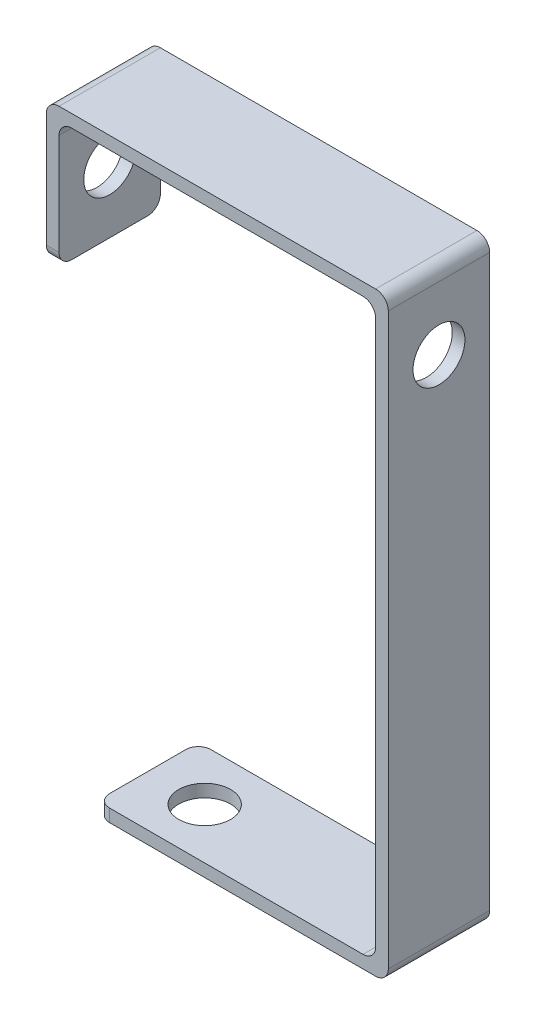
SolidWorks part; units mm, degrees
ref_plane "前视基准面" through (0, 0, 0) normal (0, 0, 1) x (1, 0, 0)
ref_plane "上视基准面" through (0, 0, 0) normal (0, 1, 0) x (1, 0, 0)
ref_plane "右视基准面" through (0, 0, 0) normal (1, 0, 0) x (0, 0, -1)
sketch "草图1" plane through (0, 0, 0) normal (0, 0, 1) x (1, 0, 0)
  line L0 (-27, -11) -> (-27, 0)
  line L1 (-27, 0) -> (0, 0)
  line L2 (0, 0) -> (0, -47)
  line L3 (0, -47) -> (-23, -47)
  dimension "D1" = 27
  dimension "D2" = 11
  dimension "D3" = 47
  dimension "D4" = 23
extrude "拉伸-薄壁1" add sketch "草图1" along normal mid plane 8 thin
sketch "草图2" plane through (0, 0, 0) normal (1, 0, 0) x (0, 0, -1)
  line L0 (-4, 0) -> (4, 0) construction
  line L1 (4, 0) -> (4, -47) construction
  circle A0 centre (0, -6) radius 2.05
  dimension "D1" = 4.1
  dimension "D2" = 6
  dimension "D3" = 4
extrude "切除-拉伸1" cut sketch "草图2" against normal through all
sketch "草图3" plane through (0, -46, 0) normal (0, 1, 0) x (1, 0, 0)
  line L0 (-23, -4) -> (-23, 4) construction
  circle A0 centre (-18.5, 0) radius 2.05
  dimension "D1" = 4.1
  dimension "D2" = 4.5
extrude "切除-拉伸2" cut sketch "草图3" against normal through all
fillet "圆角1" radius 1 4 edges at (-23, -46.5, 4) (-23, -46.5, -4) (-26.5, -11, -4) (-26.5, -11, 4)
fillet "圆角2" radius 1 4 edges at (-1, -1, 0) (0, 0, 0) (0, -47, 0) (-1, -46, 0)
fillet "圆角3" radius 1 2 edges at (-26, -1, 0) (-27, 0, 0)
